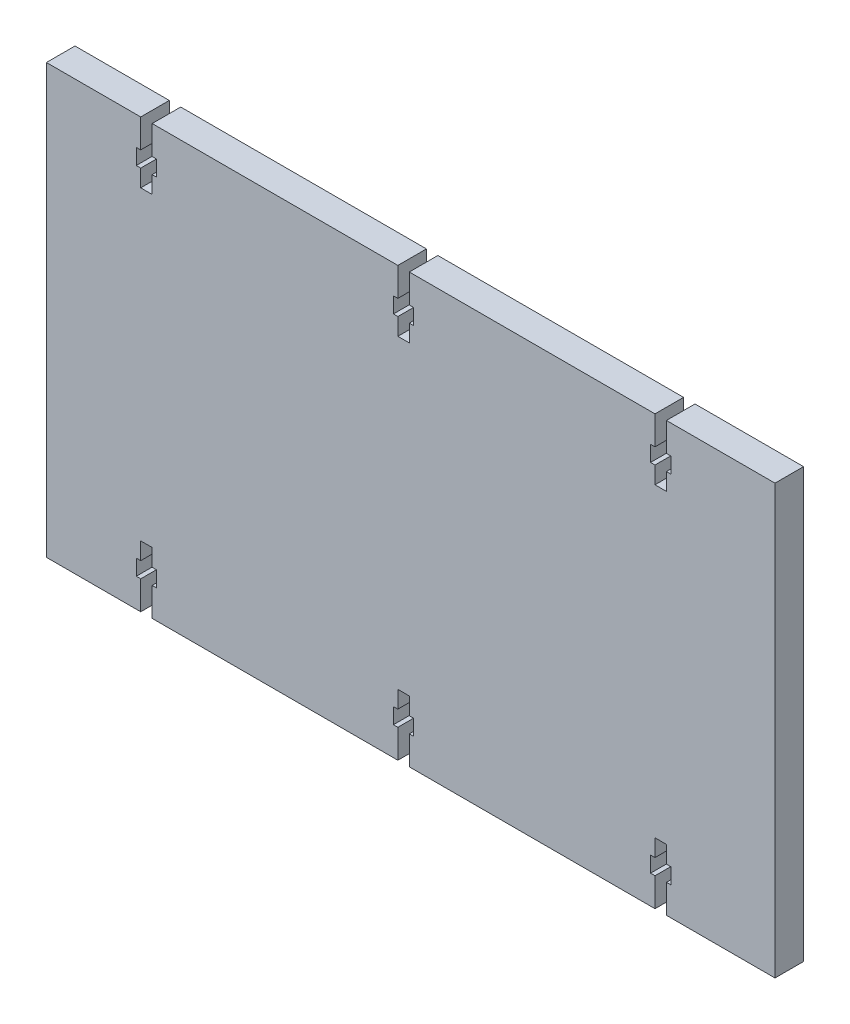
SolidWorks part; units mm, degrees
ref_plane "Plan de face" through (0, 0, 0) normal (0, 0, 1) x (1, 0, 0)
ref_plane "Plan de dessus" through (0, 0, 0) normal (0, 1, 0) x (1, 0, 0)
ref_plane "Plan de droite" through (0, 0, 0) normal (1, 0, 0) x (0, 0, -1)
sketch "Esquisse1" plane through (0, 0, 0) normal (0, 0, 1) x (1, 0, 0)
  line L1 (-127.5, 75) -> (127.5, 75)
  line L2 (-127.5, 75) -> (-127.5, -75)
  line L3 (-127.5, -75) -> (127.5, -75)
  line L4 (127.5, 75) -> (127.5, -75)
  line L5 (-127.5, 75) -> (127.5, -75) construction
  line L6 (-127.5, -75) -> (127.5, 75) construction
  point P0 (0, 0)
  dimension "D1" = 150
  dimension "D2" = 255
extrude "Boss.-Extru.1" add sketch "Esquisse1" along normal blind 10
sketch "Esquisse2" plane through (0, 0, 0) normal (0, 0, -1) x (-1, 0, 0)
  line L0 (-89.5, 75) -> (-89.5, 65)
  line L1 (-127.5, 75) -> (127.5, 75) construction
  line L2 (-89.5, 65) -> (-91.05, 65)
  line L3 (-91.05, 65) -> (-91.05, 59.5)
  line L4 (-91.05, 59.5) -> (-89.5, 59.5)
  line L5 (-89.5, 59.5) -> (-89.5, 53.5)
  line L6 (-89.5, 53.5) -> (-85.5, 53.5)
  line L7 (-87.5, 53.5) -> (-87.5, 75) construction
  line L8 (-89.5, 75) -> (-85.5, 75)
  line L9 (-85.5, 59.5) -> (-85.5, 53.5)
  line L10 (-83.95, 59.5) -> (-85.5, 59.5)
  line L11 (-83.95, 65) -> (-83.95, 59.5)
  line L12 (-85.5, 65) -> (-83.95, 65)
  line L13 (-85.5, 75) -> (-85.5, 65)
  line L14 (0.5, 75) -> (0.5, 65)
  line L15 (0.5, 65) -> (-1.05, 65)
  line L16 (-1.05, 65) -> (-1.05, 59.5)
  line L17 (-1.05, 59.5) -> (0.5, 59.5)
  line L18 (0.5, 59.5) -> (0.5, 53.5)
  line L19 (0.5, 53.5) -> (4.5, 53.5)
  line L20 (0.5, 75) -> (4.5, 75)
  line L21 (4.5, 59.5) -> (4.5, 53.5)
  line L22 (6.05, 59.5) -> (4.5, 59.5)
  line L23 (6.05, 65) -> (6.05, 59.5)
  line L24 (4.5, 65) -> (6.05, 65)
  line L25 (4.5, 75) -> (4.5, 65)
  line L26 (2.5, 53.5) -> (2.5, 75) construction
  line L27 (90.5, 75) -> (90.5, 65)
  line L28 (90.5, 65) -> (88.95, 65)
  line L29 (88.95, 65) -> (88.95, 59.5)
  line L30 (88.95, 59.5) -> (90.5, 59.5)
  line L31 (90.5, 59.5) -> (90.5, 53.5)
  line L32 (90.5, 53.5) -> (94.5, 53.5)
  line L33 (90.5, 75) -> (94.5, 75)
  line L34 (94.5, 59.5) -> (94.5, 53.5)
  line L35 (96.05, 59.5) -> (94.5, 59.5)
  line L36 (96.05, 65) -> (96.05, 59.5)
  line L37 (94.5, 65) -> (96.05, 65)
  line L38 (94.5, 75) -> (94.5, 65)
  line L39 (92.5, 53.5) -> (92.5, 75) construction
  line L40 (-127.5, 0) -> (0, 0) construction
  line L41 (-127.5, -75) -> (-127.5, 75) construction
  line L42 (92.5, -53.5) -> (92.5, -75) construction
  line L43 (2.5, -53.5) -> (2.5, -75) construction
  line L44 (-87.5, -53.5) -> (-87.5, -75) construction
  line L45 (94.5, -75) -> (94.5, -65)
  line L46 (94.5, -65) -> (96.05, -65)
  line L47 (96.05, -65) -> (96.05, -59.5)
  line L48 (96.05, -59.5) -> (94.5, -59.5)
  line L49 (94.5, -59.5) -> (94.5, -53.5)
  line L50 (90.5, -75) -> (94.5, -75)
  line L51 (90.5, -53.5) -> (94.5, -53.5)
  line L52 (90.5, -59.5) -> (90.5, -53.5)
  line L53 (88.95, -59.5) -> (90.5, -59.5)
  line L54 (88.95, -65) -> (88.95, -59.5)
  line L55 (90.5, -65) -> (88.95, -65)
  line L56 (90.5, -75) -> (90.5, -65)
  line L57 (4.5, -75) -> (4.5, -65)
  line L58 (4.5, -65) -> (6.05, -65)
  line L59 (6.05, -65) -> (6.05, -59.5)
  line L60 (6.05, -59.5) -> (4.5, -59.5)
  line L61 (4.5, -59.5) -> (4.5, -53.5)
  line L62 (0.5, -75) -> (4.5, -75)
  line L63 (0.5, -53.5) -> (4.5, -53.5)
  line L64 (0.5, -59.5) -> (0.5, -53.5)
  line L65 (-1.05, -59.5) -> (0.5, -59.5)
  line L66 (-1.05, -65) -> (-1.05, -59.5)
  line L67 (0.5, -65) -> (-1.05, -65)
  line L68 (0.5, -75) -> (0.5, -65)
  line L69 (-85.5, -75) -> (-85.5, -65)
  line L70 (-85.5, -65) -> (-83.95, -65)
  line L71 (-83.95, -65) -> (-83.95, -59.5)
  line L72 (-83.95, -59.5) -> (-85.5, -59.5)
  line L73 (-85.5, -59.5) -> (-85.5, -53.5)
  line L74 (-89.5, -75) -> (-85.5, -75)
  line L75 (-89.5, -53.5) -> (-85.5, -53.5)
  line L76 (-89.5, -59.5) -> (-89.5, -53.5)
  line L77 (-91.05, -59.5) -> (-89.5, -59.5)
  line L78 (-91.05, -65) -> (-91.05, -59.5)
  line L79 (-89.5, -65) -> (-91.05, -65)
  line L80 (-89.5, -75) -> (-89.5, -65)
  dimension "D1" = 2
  dimension "D2" = 2
  dimension "D3" = 10
  dimension "D4" = 5.5
  dimension "D5" = 6
  dimension "D6" = 7.1
  dimension "D8" = 40
  dimension "D7" = 3
extrude "Enlèv. mat.-Extru.1" cut sketch "Esquisse2" against normal blind 10
